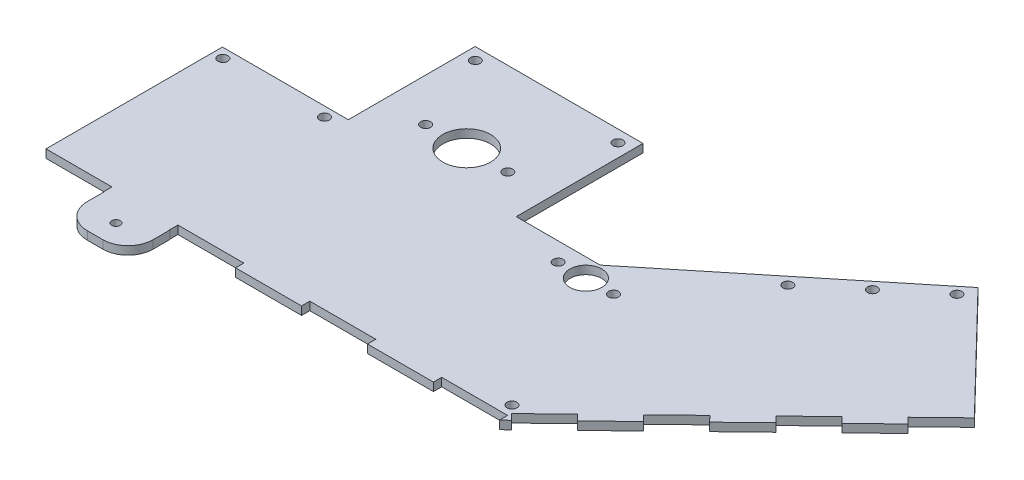
SolidWorks part; units mm, degrees
ref_plane "Front Plane" through (0, 0, 0) normal (0, 0, 1) x (1, 0, 0)
ref_plane "Top Plane" through (0, 0, 0) normal (0, 1, 0) x (1, 0, 0)
ref_plane "Right Plane" through (0, 0, 0) normal (1, 0, 0) x (0, 0, -1)
sketch "Sketch1" plane through (0, 0, 0) normal (0, 1, 0) x (1, 0, 0)
  line L0 (0, 0) -> (-38.1, 0)
  line L1 (-38.1, 0) -> (-38.1, -55.88)
  line L2 (-38.1, -55.88) -> (-18.034, -55.88)
  line L3 (101.6, -55.88) -> (174.591, 14.7944)
  line L4 (174.591, 14.7944) -> (139.2538, 51.2899)
  line L5 (139.2538, 51.2899) -> (76.2, 0)
  line L6 (76.2, 0) -> (50.8, 0)
  line L7 (50.8, 0) -> (50.8, 38.3741)
  line L8 (50.8, 38.3741) -> (0, 38.3741)
  line L9 (0, 38.3741) -> (0, 0)
  line L10 (1.905, -55.88) -> (101.6, -55.88)
  line L12 (-18.034, -55.88) -> (-18.034, -68.58)
  line L13 (-18.034, -68.58) -> (1.905, -68.58)
  line L14 (1.905, -55.88) -> (1.905, -68.58)
  line L15 (-8.0645, -68.58) -> (-8.0645, -55.88) construction
  circle A0 centre (-8.0645, -62.23) radius 1.27
  dimension "D12" = 2.54
  dimension "D1" = 50.8
  dimension "D2" = 38.1
  dimension "D3" = 25.4
  dimension "D4" = 81.28
  dimension "D5" = 50.8
  dimension "D6" = 55.88
  dimension "D7" = 101.6
  dimension "D8" = 139.7
  dimension "D9" = 20.066
  dimension "D10" = 19.939
  dimension "D11" = 12.7
extrude "Boss-Extrude1" add sketch "Sketch1" along normal blind 2.5
sketch "Sketch2" plane through (0, 2.5, 0) normal (0, 1, 0) x (1, 0, 0)
  line L0 (-38.1, -53.38) -> (101.6, -53.38) construction
  line L1 (-38.1, 0) -> (-38.1, -55.88) construction
  line L2 (-38.1, -55.88) -> (-18.034, -55.88) construction
  line L3 (-18.1429, -55.88) -> (1.8143, -55.88) construction
  line L4 (-38.1, -53.38) -> (-18.1429, -53.38)
  line L5 (-38.1, -53.38) -> (-38.1, -55.88)
  line L6 (-38.1, -55.88) -> (-18.1429, -55.88)
  line L7 (-18.1429, -53.38) -> (-18.1429, -55.88)
  line L8 (1.8143, -53.38) -> (21.7714, -53.38)
  line L9 (1.8143, -53.38) -> (1.8143, -55.88)
  line L10 (1.8143, -55.88) -> (21.7714, -55.88)
  line L11 (21.7714, -53.38) -> (21.7714, -55.88)
  line L12 (41.7286, -53.38) -> (61.6857, -53.38)
  line L13 (41.7286, -53.38) -> (41.7286, -55.88)
  line L14 (41.7286, -55.88) -> (61.6857, -55.88)
  line L15 (61.6857, -53.38) -> (61.6857, -55.88)
  line L16 (81.6429, -53.38) -> (101.6, -53.38)
  line L17 (81.6429, -53.38) -> (81.6429, -55.88)
  line L18 (81.6429, -55.88) -> (101.6, -55.88)
  line L19 (101.6, -53.38) -> (101.6, -55.88)
  line L20 (21.7714, -55.88) -> (41.7286, -55.88) construction
  line L21 (61.6857, -55.88) -> (81.6429, -55.88) construction
  dimension "D1" = 139.7
  dimension "D2" = 2.5
extrude "Cut-Extrude1" cut sketch "Sketch2" against normal blind 2.5
sketch "Sketch3" plane through (0, 2.5, 0) normal (0, 1, 0) x (1, 0, 0)
  line L0 (172.852, 16.5904) -> (101.6857, -52.3171) construction
  line L1 (174.591, 14.7944) -> (139.2538, 51.2899) construction
  line L2 (101.6, -55.88) -> (174.591, 14.7944) construction
  line L3 (101.6857, -52.3171) -> (103.4248, -54.1131)
  line L4 (103.4248, -54.1131) -> (113.5914, -44.2692)
  line L5 (113.5914, -44.2692) -> (111.8523, -42.4732)
  line L6 (111.8523, -42.4732) -> (101.6857, -52.3171)
  line L7 (122.019, -32.6292) -> (123.758, -34.4253)
  line L8 (123.758, -34.4253) -> (133.9246, -24.5813)
  line L9 (133.9246, -24.5813) -> (132.1856, -22.7853)
  line L10 (132.1856, -22.7853) -> (122.019, -32.6292)
  line L11 (142.3522, -12.9414) -> (144.0912, -14.7374)
  line L12 (144.0912, -14.7374) -> (154.2578, -4.8935)
  line L13 (154.2578, -4.8935) -> (152.5188, -3.0974)
  line L14 (152.5188, -3.0974) -> (142.3522, -12.9414)
  line L15 (162.6854, 6.7465) -> (164.4244, 4.9505)
  line L16 (164.4244, 4.9505) -> (174.591, 14.7944)
  line L17 (174.591, 14.7944) -> (172.852, 16.5904)
  line L18 (172.852, 16.5904) -> (162.6854, 6.7465)
  line L19 (113.5914, -44.2692) -> (123.758, -34.4253) construction
  line L20 (133.9246, -24.5813) -> (144.0912, -14.7374) construction
  line L21 (154.2578, -4.8935) -> (164.4244, 4.9505) construction
  dimension "D1" = 99.06
  dimension "D2" = 2.5
extrude "Cut-Extrude2" cut sketch "Sketch3" against normal blind 2.5
sketch "Sketch4" plane through (0, 2.5, 0) normal (0, 1, 0) x (1, 0, 0)
  line L0 (-38.1, -2.9327) -> (0, -2.9327) construction
  line L1 (-38.1, 0) -> (-38.1, -53.38) construction
  line L2 (0, 34.7398) -> (50.8, 34.7398) construction
  line L3 (0, 38.3741) -> (0, 0) construction
  line L4 (50.8, 0) -> (50.8, 38.3741) construction
  line L5 (141.2782, 49.1992) -> (78.4418, -2.9327) construction
  line L6 (172.852, 16.5904) -> (139.2538, 51.2899) construction
  circle A0 centre (-4.2857, -2.9327) radius 1.5
  circle A1 centre (-35.0198, -2.9327) radius 1.5
  circle A2 centre (3.7039, 34.7398) radius 1.5
  circle A3 centre (46.8569, 34.7398) radius 1.5
  circle A4 centre (137.8281, 46.3368) radius 1.5
  circle A6 centre (109.86, 23.1332) radius 1.5
  circle A7 centre (123.8498, 34.7398) radius 1.5
  dimension "D1" = 3
extrude "Cut-Extrude3" cut sketch "Sketch4" against normal blind 2.5
sketch "Sketch5" plane through (0, 2.5, 0) normal (0, 1, 0) x (1, 0, 0)
  line L0 (50.8, 38.3741) -> (0, 38.3741) construction
  line L1 (0, 38.3741) -> (0, 0) construction
  circle A0 centre (25.4, 10.4341) radius 7.239
  circle A1 centre (12.954, 10.4341) radius 1.5
  circle A2 centre (37.846, 10.4341) radius 1.5
  dimension "D1" = 14.478
  dimension "D2" = 3
  dimension "D3" = 3
  dimension "D4" = 27.94
  dimension "D5" = 25.4
  dimension "D6" = 27.94
  dimension "D7" = 27.94
  dimension "D8" = 12.446
  dimension "D9" = 12.446
extrude "Cut-Extrude4" cut sketch "Sketch5" against normal blind 2.5
sketch "Sketch6" plane through (0, 2.5, 0) normal (0, 1, 0) x (1, 0, 0)
  line L0 (76.2, 0) -> (50.8, 0) construction
  line L1 (-38.1, 0) -> (-38.1, -53.38) construction
  line L2 (77.47, -5.588) -> (94.234, -5.588) construction
  line L3 (77.47, -5.588) -> (60.706, -5.588) construction
  circle A0 centre (77.47, -5.588) radius 4.8322
  circle A1 centre (69.088, -5.588) radius 1.5
  circle A2 centre (85.852, -5.588) radius 1.5
  dimension "D3" = 3
  dimension "D4" = 3
  dimension "D1" = 5.588
  dimension "D2" = 115.57
  dimension "D5" = 8.382
  dimension "D6" = 8.382
extrude "Cut-Extrude5" cut sketch "Sketch6" against normal blind 2.5
sketch "Sketch7" plane through (0, 2.5, 0) normal (0, 1, 0) x (1, 0, 0)
  circle A0 centre (99.5255, -50.0138) radius 1.5
  dimension "D1" = 3
extrude "Cut-Extrude6" cut sketch "Sketch7" against normal blind 2.54
fillet "Fillet1" radius 7.62 2 edges at (1.905, 1.25, 68.58) (-18.034, 1.25, 68.58)
